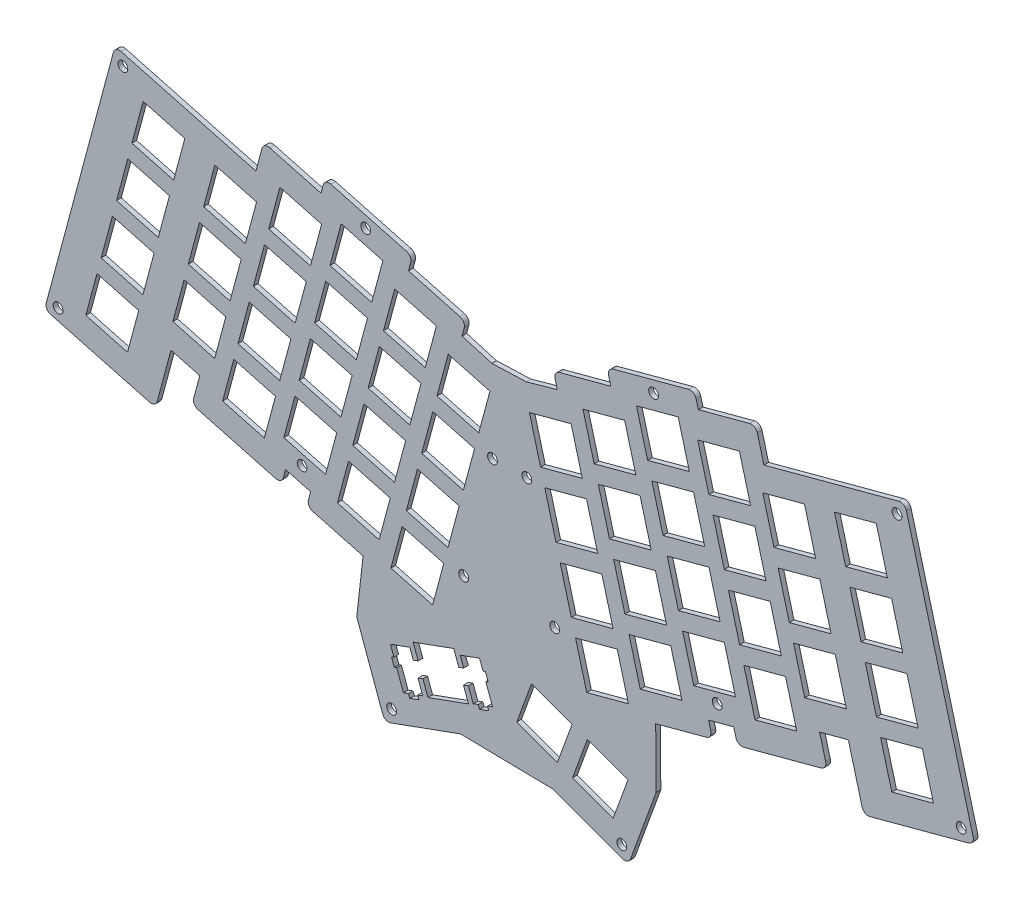
SolidWorks part; units mm, degrees
ref_plane "Front Plane" through (0, 0, 0) normal (0, 0, 1) x (1, 0, 0)
ref_plane "Top Plane" through (0, 0, 0) normal (0, 1, 0) x (1, 0, 0)
ref_plane "Right Plane" through (0, 0, 0) normal (1, 0, 0) x (0, 0, -1)
sketch "Model" plane through (0, 0, 0) normal (0, 0, 1) x (1, 0, 0)
  line L0 (282.165, 226.202) -> (288.4436, 227.8841) construction
  line L1 (267.373, 281.405) -> (273.6516, 283.0871) construction
  line L2 (195.392, 284.0785) -> (194.5766, 287.1211) construction
  line L3 (100.681, 283.685) -> (101.4961, 286.7277) construction
  line L4 (168.22, 168.742) -> (181.234, 164.006)
  line L5 (181.234, 164.006) -> (185.972, 177.021)
  line L6 (185.972, 177.021) -> (172.956, 181.758)
  line L7 (172.956, 181.758) -> (168.22, 168.742)
  line L8 (132.176, 184.752) -> (133.281, 181.717)
  line L9 (133.281, 181.717) -> (131.706, 181.144)
  line L10 (131.706, 181.144) -> (130.099, 185.56)
  line L11 (130.099, 185.56) -> (117.085, 180.823)
  line L12 (117.085, 180.823) -> (118.692, 176.407)
  line L13 (118.692, 176.407) -> (117.118, 175.834)
  line L14 (117.118, 175.834) -> (116.013, 178.869)
  line L15 (116.013, 178.869) -> (109.812, 176.612)
  line L16 (109.812, 176.612) -> (110.917, 173.576)
  line L17 (110.917, 173.576) -> (110.141, 173.294)
  line L18 (110.141, 173.294) -> (111.048, 170.804)
  line L19 (111.048, 170.804) -> (111.822, 171.086)
  line L20 (111.822, 171.086) -> (113.968, 165.194)
  line L21 (113.968, 165.194) -> (115.588, 165.784)
  line L22 (115.588, 165.784) -> (115.999, 164.656)
  line L23 (115.999, 164.656) -> (118.959, 165.734)
  line L24 (118.959, 165.734) -> (118.549, 166.861)
  line L25 (118.549, 166.861) -> (120.169, 167.452)
  line L26 (120.169, 167.452) -> (118.641, 171.651)
  line L27 (118.641, 171.651) -> (120.215, 172.224)
  line L28 (120.215, 172.224) -> (121.821, 167.809)
  line L29 (121.821, 167.809) -> (134.837, 172.545)
  line L30 (134.837, 172.545) -> (133.23, 176.962)
  line L31 (133.23, 176.962) -> (134.804, 177.535)
  line L32 (134.804, 177.535) -> (136.332, 173.335)
  line L33 (136.332, 173.335) -> (137.953, 173.925)
  line L34 (137.953, 173.925) -> (138.363, 172.796)
  line L35 (138.363, 172.796) -> (141.323, 173.874)
  line L36 (141.323, 173.874) -> (140.913, 175.001)
  line L37 (140.913, 175.001) -> (142.533, 175.592)
  line L38 (142.533, 175.592) -> (140.389, 181.483)
  line L39 (140.389, 181.483) -> (141.165, 181.766)
  line L40 (141.165, 181.766) -> (140.258, 184.256)
  line L41 (140.258, 184.256) -> (139.484, 183.974)
  line L42 (139.484, 183.974) -> (138.378, 187.009)
  line L43 (138.378, 187.009) -> (132.176, 184.752)
  line L44 (150.319, 175.258) -> (163.333, 170.521)
  line L45 (163.333, 170.521) -> (168.071, 183.535)
  line L46 (168.071, 183.535) -> (155.055, 188.273)
  line L47 (155.055, 188.273) -> (150.319, 175.258)
  line L48 (109.952, 197.835) -> (123.33, 194.251)
  line L49 (123.33, 194.251) -> (126.916, 207.629)
  line L50 (126.916, 207.629) -> (113.537, 211.213)
  line L51 (113.537, 211.213) -> (109.952, 197.835)
  line L52 (169.157, 208.022) -> (172.741, 194.644)
  line L53 (172.741, 194.644) -> (186.119, 198.228)
  line L54 (186.119, 198.228) -> (182.535, 211.607)
  line L55 (182.535, 211.607) -> (169.157, 208.022)
  line L56 (92.7848, 207.366) -> (106.163, 203.781)
  line L57 (106.163, 203.781) -> (109.747, 217.159)
  line L58 (109.747, 217.159) -> (96.369, 220.744)
  line L59 (96.369, 220.744) -> (92.7848, 207.366)
  line L60 (186.326, 217.552) -> (189.91, 204.174)
  line L61 (189.91, 204.174) -> (203.288, 207.759)
  line L62 (203.288, 207.759) -> (199.704, 221.137)
  line L63 (199.704, 221.137) -> (186.326, 217.552)
  line L64 (114.883, 216.236) -> (128.261, 212.652)
  line L65 (128.261, 212.652) -> (131.845, 226.03)
  line L66 (131.845, 226.03) -> (118.467, 229.614)
  line L67 (118.467, 229.614) -> (114.883, 216.236)
  line L68 (164.226, 226.423) -> (167.812, 213.045)
  line L69 (167.812, 213.045) -> (181.19, 216.629)
  line L70 (181.19, 216.629) -> (177.604, 230.007)
  line L71 (177.604, 230.007) -> (164.226, 226.423)
  line L72 (75.6158, 216.896) -> (88.9938, 213.312)
  line L73 (88.9938, 213.312) -> (92.5781, 226.69)
  line L74 (92.5781, 226.69) -> (79.2, 230.274)
  line L75 (79.2, 230.274) -> (75.6158, 216.896)
  line L76 (55.9827, 217.227) -> (69.3607, 213.643)
  line L77 (69.3607, 213.643) -> (72.9449, 227.021)
  line L78 (72.9449, 227.021) -> (59.5672, 230.605)
  line L79 (59.5672, 230.605) -> (55.9827, 217.227)
  line L80 (203.494, 227.083) -> (207.078, 213.705)
  line L81 (207.078, 213.705) -> (220.457, 217.29)
  line L82 (220.457, 217.29) -> (216.872, 230.668)
  line L83 (216.872, 230.668) -> (203.494, 227.083)
  line L84 (223.128, 227.414) -> (226.712, 214.036)
  line L85 (226.712, 214.036) -> (240.09, 217.62)
  line L86 (240.09, 217.62) -> (236.506, 230.998)
  line L87 (236.506, 230.998) -> (223.128, 227.414)
  line L88 (12.1157, 219.121) -> (25.4937, 215.536)
  line L89 (25.4937, 215.536) -> (29.078, 228.914)
  line L90 (29.078, 228.914) -> (15.7, 232.499)
  line L91 (15.7, 232.499) -> (12.1157, 219.121)
  line L92 (266.995, 229.307) -> (270.579, 215.929)
  line L93 (270.579, 215.929) -> (283.957, 219.513)
  line L94 (283.957, 219.513) -> (280.373, 232.891)
  line L95 (280.373, 232.891) -> (266.995, 229.307)
  line L96 (97.7138, 225.767) -> (111.092, 222.183)
  line L97 (111.092, 222.183) -> (114.677, 235.56)
  line L98 (114.677, 235.56) -> (101.299, 239.145)
  line L99 (101.299, 239.145) -> (97.7138, 225.767)
  line L100 (181.394, 235.953) -> (184.98, 222.575)
  line L101 (184.98, 222.575) -> (198.357, 226.159)
  line L102 (198.357, 226.159) -> (194.773, 239.538)
  line L103 (194.773, 239.538) -> (181.394, 235.953)
  line L104 (40.0473, 231.357) -> (53.425, 227.773)
  line L105 (53.425, 227.773) -> (57.0096, 241.151)
  line L106 (57.0096, 241.151) -> (43.6316, 244.735)
  line L107 (43.6316, 244.735) -> (40.0473, 231.357)
  line L108 (239.062, 241.545) -> (242.648, 228.166)
  line L109 (242.648, 228.166) -> (256.024, 231.75)
  line L110 (256.024, 231.75) -> (252.44, 245.128)
  line L111 (252.44, 245.128) -> (239.062, 241.545)
  line L112 (119.814, 234.637) -> (133.192, 231.053)
  line L113 (133.192, 231.053) -> (136.776, 244.431)
  line L114 (136.776, 244.431) -> (123.396, 248.015)
  line L115 (123.396, 248.015) -> (119.814, 234.637)
  line L116 (159.297, 244.824) -> (162.88, 231.445)
  line L117 (162.88, 231.445) -> (176.258, 235.03)
  line L118 (176.258, 235.03) -> (172.675, 248.408)
  line L119 (172.675, 248.408) -> (159.297, 244.824)
  line L120 (80.5462, 235.297) -> (93.9243, 231.713)
  line L121 (93.9243, 231.713) -> (97.5099, 245.091)
  line L122 (97.5099, 245.091) -> (84.1304, 248.675)
  line L123 (84.1304, 248.675) -> (80.5462, 235.297)
  line L124 (60.912, 235.628) -> (74.2901, 232.044)
  line L125 (74.2901, 232.044) -> (77.8757, 245.422)
  line L126 (77.8757, 245.422) -> (64.4977, 249.006)
  line L127 (64.4977, 249.006) -> (60.912, 235.628)
  line L128 (198.563, 245.484) -> (202.147, 232.106)
  line L129 (202.147, 232.106) -> (215.525, 235.692)
  line L130 (215.525, 235.692) -> (211.941, 249.069)
  line L131 (211.941, 249.069) -> (198.563, 245.484)
  line L132 (218.196, 245.814) -> (221.782, 232.436)
  line L133 (221.782, 232.436) -> (235.16, 236.021)
  line L134 (235.16, 236.021) -> (231.574, 249.399)
  line L135 (231.574, 249.399) -> (218.196, 245.814)
  line L136 (17.045, 237.521) -> (30.423, 233.937)
  line L137 (30.423, 233.937) -> (34.0086, 247.315)
  line L138 (34.0086, 247.315) -> (20.6306, 250.899)
  line L139 (20.6306, 250.899) -> (17.045, 237.521)
  line L140 (262.063, 247.708) -> (265.649, 234.33)
  line L141 (265.649, 234.33) -> (279.026, 237.914)
  line L142 (279.026, 237.914) -> (275.442, 251.292)
  line L143 (275.442, 251.292) -> (262.063, 247.708)
  line L144 (102.646, 244.168) -> (116.024, 240.584)
  line L145 (116.024, 240.584) -> (119.607, 253.962)
  line L146 (119.607, 253.962) -> (106.229, 257.546)
  line L147 (106.229, 257.546) -> (102.646, 244.168)
  line L148 (176.465, 254.354) -> (180.049, 240.976)
  line L149 (180.049, 240.976) -> (193.427, 244.56)
  line L150 (193.427, 244.56) -> (189.843, 257.938)
  line L151 (189.843, 257.938) -> (176.465, 254.354)
  line L152 (44.9778, 249.759) -> (58.3558, 246.174)
  line L153 (58.3558, 246.174) -> (61.94, 259.553)
  line L154 (61.94, 259.553) -> (48.562, 263.136)
  line L155 (48.562, 263.136) -> (44.9778, 249.759)
  line L156 (234.133, 259.945) -> (237.717, 246.567)
  line L157 (237.717, 246.567) -> (251.095, 250.151)
  line L158 (251.095, 250.151) -> (247.511, 263.529)
  line L159 (247.511, 263.529) -> (234.133, 259.945)
  line L160 (124.743, 253.038) -> (138.122, 249.454)
  line L161 (138.122, 249.454) -> (141.707, 262.832)
  line L162 (141.707, 262.832) -> (128.329, 266.416)
  line L163 (128.329, 266.416) -> (124.743, 253.038)
  line L164 (154.365, 263.224) -> (157.951, 249.845)
  line L165 (157.951, 249.845) -> (171.329, 253.432)
  line L166 (171.329, 253.432) -> (167.743, 266.809)
  line L167 (167.743, 266.809) -> (154.365, 263.224)
  line L168 (85.477, 253.699) -> (98.855, 250.114)
  line L169 (98.855, 250.114) -> (102.439, 263.492)
  line L170 (102.439, 263.492) -> (89.0612, 267.076)
  line L171 (89.0612, 267.076) -> (85.477, 253.699)
  line L172 (65.8442, 254.03) -> (79.2219, 250.443)
  line L173 (79.2219, 250.443) -> (82.8065, 263.823)
  line L174 (82.8065, 263.823) -> (69.427, 267.407)
  line L175 (69.427, 267.407) -> (65.8442, 254.03)
  line L176 (193.632, 263.885) -> (197.218, 250.507)
  line L177 (197.218, 250.507) -> (210.596, 254.092)
  line L178 (210.596, 254.092) -> (207.01, 267.47)
  line L179 (207.01, 267.47) -> (193.632, 263.885)
  line L180 (213.267, 264.215) -> (216.851, 250.837)
  line L181 (216.851, 250.837) -> (230.229, 254.422)
  line L182 (230.229, 254.422) -> (226.645, 267.8)
  line L183 (226.645, 267.8) -> (213.267, 264.215)
  line L184 (21.977, 255.922) -> (35.355, 252.338)
  line L185 (35.355, 252.338) -> (38.9378, 265.716)
  line L186 (38.9378, 265.716) -> (25.5598, 269.3)
  line L187 (25.5598, 269.3) -> (21.977, 255.922)
  line L188 (257.132, 266.109) -> (260.718, 252.729)
  line L189 (260.718, 252.729) -> (274.096, 256.315)
  line L190 (274.096, 256.315) -> (270.512, 269.693)
  line L191 (270.512, 269.693) -> (257.132, 266.109)
  line L192 (107.575, 262.569) -> (120.953, 258.984)
  line L193 (120.953, 258.984) -> (124.539, 272.362)
  line L194 (124.539, 272.362) -> (111.161, 275.947)
  line L195 (111.161, 275.947) -> (107.575, 262.569)
  line L196 (171.534, 272.755) -> (175.118, 259.377)
  line L197 (175.118, 259.377) -> (188.496, 262.961)
  line L198 (188.496, 262.961) -> (184.912, 276.339)
  line L199 (184.912, 276.339) -> (171.534, 272.755)
  line L200 (49.9071, 268.159) -> (63.2852, 264.575)
  line L201 (63.2852, 264.575) -> (66.8708, 277.953)
  line L202 (66.8708, 277.953) -> (53.4928, 281.537)
  line L203 (53.4928, 281.537) -> (49.9071, 268.159)
  line L204 (229.201, 278.346) -> (232.786, 264.968)
  line L205 (232.786, 264.968) -> (246.164, 268.554)
  line L206 (246.164, 268.554) -> (242.579, 281.932)
  line L207 (242.579, 281.932) -> (229.201, 278.346)
  line L208 (90.4074, 272.099) -> (103.785, 268.515)
  line L209 (103.785, 268.515) -> (107.37, 281.893)
  line L210 (107.37, 281.893) -> (93.992, 285.477)
  line L211 (93.992, 285.477) -> (90.4074, 272.099)
  line L212 (70.7732, 272.43) -> (84.1513, 268.844)
  line L213 (84.1513, 268.844) -> (87.7369, 282.222)
  line L214 (87.7369, 282.222) -> (74.3589, 285.808)
  line L215 (74.3589, 285.808) -> (70.7732, 272.43)
  line L216 (188.703, 282.286) -> (192.286, 268.908)
  line L217 (192.286, 268.908) -> (205.664, 272.493)
  line L218 (205.664, 272.493) -> (202.081, 285.871)
  line L219 (202.081, 285.871) -> (188.703, 282.286)
  line L220 (208.336, 282.616) -> (211.92, 269.238)
  line L221 (211.92, 269.238) -> (225.298, 272.822)
  line L222 (225.298, 272.822) -> (221.714, 286.2)
  line L223 (221.714, 286.2) -> (208.336, 282.616)
  line L224 (26.9062, 274.323) -> (40.284, 270.739)
  line L225 (40.284, 270.739) -> (43.8697, 284.117)
  line L226 (43.8697, 284.117) -> (30.4919, 287.701)
  line L227 (30.4919, 287.701) -> (26.9062, 274.323)
  line L228 (252.203, 284.508) -> (255.786, 271.131)
  line L229 (255.786, 271.131) -> (269.165, 274.716)
  line L230 (269.165, 274.716) -> (265.581, 288.094)
  line L231 (265.581, 288.094) -> (252.203, 284.508)
  line L232 (37.1808, 285.909) -> (37.996, 288.9517) construction
  line L233 (28.6991, 281.012) -> (22.4207, 282.6948) construction
  line L234 (18.8047, 217.3285) -> (17.9893, 214.2859) construction
  line L235 (13.9078, 225.81) -> (7.6293, 227.4922) construction
  line L236 (277.268, 217.721) -> (278.0831, 214.6783) construction
  line L237 (271.2033, 292.224) -> (291.0512, 218.1525) construction
  line L238 (241.3027, 224.5444) -> (243.7675, 215.3441) construction
  line L239 (81.0479, 284.015) -> (81.8635, 287.0576) construction
  line L240 (181.234, 164.006) -> (184.194, 162.9285) construction
  line L241 (91.0631, 284.5916) -> (72.6639, 289.5236) construction
  line L242 (117.85, 274.1545) -> (118.6654, 277.1971) construction
  line L243 (135.018, 264.624) -> (135.8331, 267.6667) construction
  line L244 (161.054, 265.0165) -> (160.2386, 268.0591) construction
  line L245 (178.223, 274.547) -> (177.4079, 277.5897) construction
  line L246 (215.025, 284.408) -> (214.2099, 287.4507) construction
  line L247 (258.892, 286.301) -> (258.2357, 288.7493) construction
  line L248 (196.599, 205.9665) -> (197.4144, 202.9239) construction
  line L249 (92.2965, 289.1937) -> (110.6958, 284.2617) construction
  line L250 (213.7675, 215.4975) -> (214.5828, 212.4548) construction
  line L251 (233.401, 215.828) -> (234.2161, 212.7853) construction
  line L252 (62.6717, 215.435) -> (61.8566, 212.3923) construction
  line L253 (82.3048, 215.104) -> (81.4897, 212.0613) construction
  line L254 (99.4739, 205.5735) -> (98.6586, 202.5309) construction
  line L255 (35.8867, 229.2106) -> (54.7701, 224.1516) construction
  line L256 (60.1818, 279.745) -> (60.9969, 282.7877) construction
  line L257 (72.6639, 289.5236) -> (70.1982, 280.3232) construction
  line L258 (105.8147, 195.273) -> (104.0964, 179.4507) construction
  line L259 (52.3052, 214.9511) -> (54.7701, 224.1516) construction
  line L260 (260.1862, 229.6041) -> (265.1156, 211.2042) construction
  line L261 (203.777, 289.5866) -> (185.3762, 284.6556) construction
  line L262 (30.9571, 210.8115) -> (35.8867, 229.2106) construction
  line L263 (141.707, 262.832) -> (142.5224, 265.8746) construction
  line L264 (154.365, 263.224) -> (153.5495, 266.2666) construction
  line L265 (181.234, 164.006) -> (180.1565, 161.046) construction
  line L266 (92.2965, 289.1937) -> (91.0631, 284.5916) construction
  line L267 (169.4396, 270.5248) -> (150.6904, 265.5004) construction
  line L268 (110.6958, 284.2617) -> (109.4634, 279.6637) construction
  line L269 (127.8626, 274.7318) -> (126.6303, 270.1341) construction
  line L270 (127.8626, 274.7318) -> (109.4634, 279.6637) construction
  line L271 (260.1862, 229.6041) -> (241.3027, 224.5444) construction
  line L272 (126.6303, 270.1341) -> (145.3813, 265.1084) construction
  line L273 (185.3762, 284.6556) -> (186.6084, 280.0546) construction
  line L274 (142.3447, 270.8715) -> (153.3719, 271.2634)
  line L275 (203.777, 289.5866) -> (205.0099, 284.986) construction
  line L276 (168.2073, 275.1248) -> (169.4396, 270.5248) construction
  line L277 (205.0099, 284.986) -> (223.4098, 289.9154) construction
  line L278 (223.4098, 289.9154) -> (226.0339, 280.1206) construction
  line L279 (186.6084, 280.0546) -> (168.2073, 275.1248) construction
  line L280 (104.0964, 179.4507) -> (110.9864, 160.5147) construction
  line L281 (152.687, 181.7655) -> (183.603, 170.5135) construction
  line L282 (110.5015, 171.0598) -> (141.4185, 182.3092) construction
  line L283 (27.2858, 222.225) -> (33.5644, 220.5428) construction
  line L284 (90.3394, 209.6904) -> (72.6399, 214.4322) construction
  line L285 (71.4079, 209.8335) -> (72.6399, 214.4322) construction
  line L286 (89.1069, 205.0898) -> (90.3394, 209.6904) construction
  line L287 (89.1069, 205.0898) -> (107.1497, 200.256) construction
  line L288 (107.1497, 200.256) -> (105.8147, 195.273) construction
  line L289 (110.9864, 160.5147) -> (131.4289, 167.9529) construction
  line L290 (71.4079, 209.8335) -> (52.3052, 214.9511) construction
  line L291 (5.0216, 217.7602) -> (25.0282, 292.4264) construction
  line L292 (130.099, 185.56) -> (121.821, 167.809) construction
  line L293 (190.0384, 195.7708) -> (190.0096, 178.9037) construction
  line L294 (235.89, 280.139) -> (235.2337, 282.5873) construction
  line L295 (162.6744, 167.408) -> (183.1165, 159.9688) construction
  line L296 (131.4289, 167.9529) -> (162.6744, 167.408) construction
  line L297 (5.0216, 217.7602) -> (30.9571, 210.8115) construction
  line L298 (46.7361, 229.565) -> (45.921, 226.5223) construction
  line L299 (265.1156, 211.2042) -> (291.0512, 218.1525) construction
  line L300 (25.0282, 292.4264) -> (70.1982, 280.3232) construction
  line L301 (226.0339, 280.1206) -> (258.2357, 288.7493) construction
  line L302 (258.2357, 288.7493) -> (271.2033, 292.224) construction
  line L303 (128.329, 170.177) -> (129.4061, 167.2169) construction
  line L304 (249.336, 229.958) -> (250.1513, 226.9153) construction
  line L305 (268.787, 222.618) -> (262.5084, 220.9359) construction
  line L306 (109.952, 197.835) -> (106.7322, 198.6976) construction
  line L307 (-1.1021, 214.2246) -> (21.4927, 298.5501)
  line L308 (186.119, 198.228) -> (189.1617, 199.0431) construction
  line L309 (206.9661, 205.4835) -> (188.7445, 200.6005) construction
  line L310 (188.7445, 200.6005) -> (190.0384, 195.7708) construction
  line L311 (21.4927, 298.5501) -> (66.6629, 286.4469)
  line L312 (69.1286, 295.6477) -> (66.6629, 286.4469)
  line L313 (87.528, 290.7157) -> (69.1286, 295.6477)
  line L314 (88.7615, 295.3178) -> (87.528, 290.7157)
  line L315 (88.7615, 295.3178) -> (116.8197, 287.7967)
  line L316 (116.8197, 287.7967) -> (115.5873, 283.1987)
  line L317 (133.9865, 278.2668) -> (115.5873, 283.1987)
  line L318 (133.9865, 278.2668) -> (132.7543, 273.6692)
  line L319 (132.7543, 273.6692) -> (142.3447, 270.8715)
  line L320 (153.3719, 271.2634) -> (163.3162, 274.0603)
  line L321 (21.4927, 298.5501) -> (25.0282, 292.4264) construction
  line L322 (162.0837, 278.6606) -> (163.3162, 274.0603)
  line L323 (180.4853, 283.5905) -> (162.0837, 278.6606)
  line L324 (179.2532, 288.1912) -> (180.4853, 283.5905)
  line L325 (207.3124, 295.7105) -> (179.2532, 288.1912)
  line L326 (207.3124, 295.7105) -> (208.5454, 291.1095)
  line L327 (208.5454, 291.1095) -> (226.9456, 296.039)
  line L328 (226.9456, 296.039) -> (229.5696, 286.2444)
  line L329 (229.5696, 286.2444) -> (274.7388, 298.3478)
  line L330 (297.175, 214.6167) -> (292.845, 217.1168) construction
  line L331 (274.7388, 298.3478) -> (297.175, 214.6167)
  line L332 (261.5798, 205.0807) -> (297.175, 214.6167)
  line L333 (256.6504, 223.4803) -> (261.5798, 205.0807)
  line L334 (256.6504, 223.4803) -> (247.4262, 221.0088)
  line L335 (183.1165, 159.9688) -> (190.0096, 178.9037) construction
  line L336 (247.4262, 221.0088) -> (249.8911, 211.8083)
  line L337 (221.1293, 204.103) -> (249.8911, 211.8083)
  line L338 (219.8969, 208.7022) -> (221.1293, 204.103)
  line L339 (211.8572, 206.5483) -> (219.8969, 208.7022)
  line L340 (206.9661, 205.4835) -> (205.7333, 210.084) construction
  line L341 (223.4323, 214.8256) -> (224.6648, 210.2265) construction
  line L342 (205.7333, 210.084) -> (223.4323, 214.8256) construction
  line L343 (213.0899, 201.9481) -> (211.8572, 206.5483)
  line L344 (213.0899, 201.9481) -> (194.868, 197.0651)
  line L345 (224.6648, 210.2265) -> (243.7675, 215.3441) construction
  line L346 (194.868, 197.0651) -> (195.0081, 178.0178)
  line L347 (150.6904, 265.5004) -> (170.7656, 190.6076) construction
  line L348 (186.1047, 153.5606) -> (195.0081, 178.0178)
  line L349 (161.7507, 162.4234) -> (186.1047, 153.5606)
  line L350 (132.268, 162.9375) -> (161.7507, 162.4234)
  line L351 (107.9974, 154.1064) -> (132.268, 162.9375)
  line L352 (99, 178.8342) -> (107.9974, 154.1064)
  line L353 (101.0261, 196.7202) -> (99, 178.8342)
  line L354 (141.707, 262.832) -> (154.365, 263.224) construction
  line L355 (82.9833, 201.554) -> (101.0261, 196.7202)
  line L356 (82.9833, 201.554) -> (84.2158, 206.1546)
  line L357 (84.2158, 206.1546) -> (76.1757, 208.3086)
  line L358 (74.9437, 203.7099) -> (76.1757, 208.3086)
  line L359 (74.9437, 203.7099) -> (46.1816, 211.4153)
  line L360 (46.1816, 211.4153) -> (48.6465, 220.6158)
  line L361 (39.4224, 223.087) -> (48.6465, 220.6158)
  line L362 (34.4928, 204.6878) -> (39.4224, 223.087)
  line L363 (-1.1021, 214.2246) -> (34.4928, 204.6878)
  line L364 (21.4927, 298.5501) -> (23.9927, 294.22) construction
  line L365 (142.5224, 265.8746) -> (153.5495, 266.2666) construction
  line L366 (274.7388, 298.3478) -> (271.2033, 292.224) construction
  line L367 (291.0512, 218.1525) -> (297.175, 214.6167) construction
  line L368 (-1.1021, 214.2246) -> (5.0216, 217.7602) construction
  line L369 (107.9974, 154.1064) -> (110.9864, 160.5147) construction
  line L370 (183.1165, 159.9688) -> (186.1047, 153.5606) construction
  line L371 (107.9974, 154.1064) -> (110.1779, 158.7812) construction
  line L372 (183.9916, 158.0921) -> (186.1047, 153.5606) construction
  line L373 (106.163, 203.781) -> (189.91, 204.174) construction
  line L374 (101.4961, 286.7277) -> (102.7906, 291.5572) construction
  line L375 (194.5766, 287.1211) -> (193.2828, 291.9508) construction
  line L376 (23.9927, 294.22) -> (24.9077, 297.635) construction
  line L377 (193.2828, 291.9508) -> (194.1977, 288.5357) construction
  line L378 (214.5828, 212.4548) -> (215.877, 207.6252) construction
  line L379 (102.7906, 291.5572) -> (101.8753, 288.1422) construction
  line L380 (274.7388, 298.3478) -> (272.2388, 294.0176) construction
  line L381 (-1.1021, 214.2246) -> (3.228, 216.7246) construction
  line L382 (81.4897, 212.0613) -> (80.1958, 207.2316) construction
  line L383 (81.4897, 212.0613) -> (80.1958, 207.2316) construction
  line L384 (214.5828, 212.4548) -> (215.877, 207.6252) construction
  line L385 (145.3813, 265.1084) -> (125.265, 190.0622) construction
  line L386 (190.0384, 195.7708) -> (170.7656, 190.6076) construction
  line L387 (148.0359, 266.0706) -> (148.0365, 203.9775) construction
  line L388 (105.8147, 195.273) -> (125.265, 190.0622) construction
  line L389 (104.0964, 179.4507) -> (140.9309, 192.8582) construction
  line L390 (190.0096, 178.9037) -> (153.1726, 192.3111) construction
  line L391 (152.687, 181.7655) -> (149.727, 182.8428) construction
  line L392 (162.6744, 167.408) -> (146.281, 173.3738) construction
  line L393 (153.1726, 192.3111) -> (146.281, 173.3738) construction
  line L394 (131.4289, 167.9529) -> (147.823, 173.9234) construction
  line L395 (141.4185, 182.3092) -> (144.3786, 183.3863) construction
  line L396 (140.9309, 192.8582) -> (147.823, 173.9234) construction
  line L397 (110.5015, 171.0598) -> (107.5414, 169.9827) construction
  line L398 (123.592, 183.1915) -> (122.5136, 186.1545) construction
  line L399 (105.8147, 195.273) -> (183.187, 229.264) construction
  line L400 (171.073, 185.7954) -> (164.1828, 166.8591) construction
  line L401 (112.8845, 228.8715) -> (190.0384, 195.7708) construction
  line L402 (105.8147, 195.273) -> (133.2811, 207.3395) construction
  line L403 (162.4685, 207.5989) -> (190.0384, 195.7708) construction
  line L404 (136.776, 244.431) -> (159.297, 244.824) construction
  line L405 (136.776, 244.431) -> (142.5224, 244.5313) construction
  line L406 (159.297, 244.824) -> (153.5495, 244.7237) construction
  line L425 (164.1828, 166.8591) -> (183.1165, 159.9688) construction
  line L426 (190.0096, 178.9037) -> (171.073, 185.7954) construction
  line L427 (101.0261, 196.7202) -> (100.8855, 196.1953) construction
  line L428 (100.8855, 196.1953) -> (99, 178.8342) construction
  line L429 (150.6904, 265.5004) -> (145.3813, 265.1084) construction
  line L430 (149.8518, 270.4521) -> (145.8577, 270.1572) construction
  line L431 (132.7543, 273.6692) -> (145.8577, 270.1572) construction
  line L432 (163.3162, 274.0603) -> (149.8518, 270.4521) construction
  line L433 (256.9416, 293.5789) -> (274.7388, 298.3478) construction
  line L434 (229.5696, 286.2444) -> (256.9416, 293.5789) construction
  line L435 (194.868, 197.0651) -> (195.0395, 196.4248) construction
  line L436 (195.0395, 196.4248) -> (195.0081, 178.0178) construction
  circle A0 centre (23.9927, 294.22) radius 1.575
  circle A1 centre (110.1779, 158.7812) radius 1.575
  circle A2 centre (183.9916, 158.0921) radius 1.575
  circle A3 centre (194.1977, 288.5357) radius 1.575
  circle A4 centre (101.8753, 288.1422) radius 1.575
  circle A5 centre (272.2388, 294.0176) radius 1.5916
  circle A6 centre (3.228, 216.7246) radius 1.575
  circle A7 centre (292.845, 217.1168) radius 1.5916
  circle A8 centre (81.4897, 212.0613) radius 1.575
  circle A9 centre (214.5828, 212.4548) radius 1.575
  circle A10 centre (133.2811, 207.3395) radius 1.575
  circle A11 centre (162.4685, 207.5989) radius 1.575
  circle A12 centre (142.5224, 244.5313) radius 1.575
  circle A13 centre (153.5495, 244.7237) radius 1.575
  point P253 (61.8566, 212.3923)
  point P289 (81.8635, 287.0576)
  point P293 (194.5766, 287.1211)
  point P295 (101.4961, 286.7277)
  point P297 (81.4897, 212.0613)
  point P361 (125.96, 176.6845)
  point P362 (125.96, 176.6845)
  point P374 (214.5828, 212.4548)
  point P377 (234.2161, 212.7853)
  point P378 (177.4079, 277.5897)
  point P386 (214.2099, 287.4507)
  dimension "D5" = 5
  dimension "D4" = 3.15
  dimension "D7" = 30.011
  dimension "D8" = 30
  dimension "D1" = 9.5249
  dimension "D2" = 6.5
  dimension "D3" = 5
  dimension "D6" = 5
extrude "Boss-Extrude1" add sketch "Model" against normal blind 1.5
fillet "Fillet2" radius 2 22 edges at (-1.1021, 214.2246, -0.75) (46.1816, 211.4153, -0.75) (34.4928, 204.6878, -0.75) (74.9437, 203.7099, -0.75) (82.9833, 201.554, -0.75) (107.9974, 154.1064, -0.75) (221.1293, 204.103, -0.75) (213.0899, 201.9481, -0.75) (186.1047, 153.5606, -0.75) (261.5798, 205.0807, -0.75) (249.8911, 211.8083, -0.75) (297.175, 214.6167, -0.75) (274.7388, 298.3478, -0.75) (226.9456, 296.039, -0.75) (207.3124, 295.7105, -0.75) (179.2532, 288.1912, -0.75) (162.0837, 278.6606, -0.75) (133.9865, 278.2668, -0.75) (116.8197, 287.7967, -0.75) (88.7615, 295.3178, -0.75) (69.1286, 295.6477, -0.75) (21.4927, 298.5501, -0.75)
